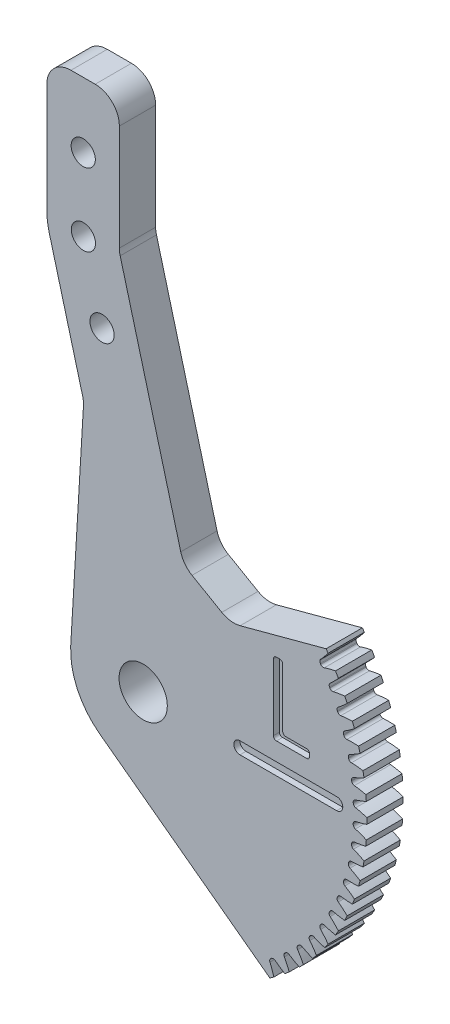
SolidWorks part; units mm, degrees
material "Delrin 2700 NC010, Low Viscosity Acetal Copolymer (SS)"
ref_plane "Front Plane" through (0, 0, 0) normal (0, 0, 1) x (1, 0, 0)
ref_plane "Top Plane" through (0, 0, 0) normal (0, 1, 0) x (1, 0, 0)
ref_plane "Right Plane" through (0, 0, 0) normal (1, 0, 0) x (0, 0, -1)
sketch "Sketch2" plane through (0, 0, 0) normal (0, 0, 1) x (1, 0, 0)
  circle A0 centre (0, 0) radius 60.325
  dimension "D1" = 120.65
extrude "Boss-Extrude2" add sketch "Sketch2" along normal mid plane 9.525
sketch "Sketch3" plane through (0, 0, 4.7625) normal (0, 0, 1) x (1, 0, 0)
  line L0 (0, 0) -> (-57.8242, 215.8028) construction
  line L1 (0, 0) -> (60.325, 0) construction
  line L2 (-15.6133, 58.2695) -> (-24.6525, 92.0044)
  line L3 (-24.6525, 92.0044) -> (-6.2516, 96.9349)
  line L4 (-6.2516, 96.9349) -> (3.5866, 60.2183)
  circle A0 centre (0, 0) radius 60.325 construction
  arc A1 (3.5866, 60.2183) -> (-15.6133, 58.2695) centre (0, 0) ccw
  point P9 (0, 0)
  point P11 (0, 0)
  dimension "D1" = 105
  dimension "D2" = 19.05
  dimension "D3" = 95.25
extrude "Boss-Extrude3" add sketch "Sketch3" against normal up to surface (9.525 mm away) up to face at (60.325, 0, -4.7625)
sketch "Sketch4" plane through (0, 0, 4.7625) normal (0, 0, 1) x (1, 0, 0)
  line L0 (-6.2516, 96.9349) -> (-25.3016, 96.9349)
  line L1 (-25.3016, 96.9349) -> (-25.3016, 131.8599)
  line L2 (-25.3016, 131.8599) -> (-6.2516, 131.8599)
  line L3 (-6.2516, 131.8599) -> (-6.2516, 96.9349)
  line L4 (3.5866, 60.2183) -> (-6.2516, 96.9349) construction
  dimension "D3" = 34.925
  dimension "D1" = 19.05
  dimension "D2" = 165
extrude "Boss-Extrude4" add sketch "Sketch4" against normal up to surface (9.525 mm away) separate body
sketch "Sketch5" plane through (0, 0, 4.7625) normal (0, 0, 1) x (1, 0, 0)
  line L0 (-25.3016, 96.9349) -> (-6.2516, 96.9349) construction
  line L1 (-6.2516, 96.9349) -> (-24.6525, 92.0044) construction
  line L2 (-25.3016, 96.9349) -> (-6.2516, 96.9349)
  line L3 (-6.2516, 96.9349) -> (-24.6525, 92.0044)
  arc A0 (-25.3016, 96.9349) -> (-24.6525, 92.0044) centre (-6.2516, 96.9349) ccw
extrude "Boss-Extrude5" add sketch "Sketch5" against normal up to surface (9.525 mm away)
hole_wizard "1/2 (0.5) Diameter Hole1" positions "Sketch6" profile "Sketch7" hole size "1/2" standard "ANSI Inch" end condition through all
sketch "Sketch6" plane through (0, 0, 4.7625) normal (0, 0, 1) x (1, 0, 0)
  point P0 (0, 0)
sketch "Sketch7" plane through (0, 0, 4.7625) normal (1, 0, 0) x (0, -1, 0)
  line L0 (0, 0) -> (0, 9.525)
  line L1 (0, 9.525) -> (6.3373, 9.525)
  line L2 (6.3373, 9.525) -> (6.3373, 0)
  line L5 (6.3373, 0) -> (0, 0)
  line L11 (0, -6.35) -> (0, 107.95) construction
  dimension "Thru Hole Dia." = 12.6746
  dimension "Thru Hole Depth" = 9.525
sketch "Sketch8" plane through (0, 0, 4.7625) normal (0, 0, 1) x (1, 0, 0)
  line L0 (0, 0) -> (58.2695, 15.6133) construction
  line L1 (-24.6525, 92.0044) -> (-15.6133, 58.2695) construction
  line L2 (22.9188, 27.0957) -> (49.653, 34.2591)
  line L3 (22.9188, 27.0957) -> (10.548, 34.2381)
  line L4 (3.5866, 60.2183) -> (10.548, 34.2381)
  line L5 (3.5866, 60.2183) -> (-6.2516, 96.9349) construction
  line L7 (-5.2387, 19.5509) -> (53.0308, 35.1642) construction
  arc A0 (-15.6133, 58.2695) -> (3.5866, 60.2183) centre (0, 0) ccw construction
  arc A1 (49.653, 34.2591) -> (3.5866, 60.2183) centre (0, 0) ccw
  dimension "D2" = 45
  dimension "D3" = 34.925
  dimension "D1" = 20.2406
extrude "Cut-Extrude1" cut sketch "Sketch8" against normal through all
sketch "Sketch9" plane through (0, 0, 4.7625) normal (0, 0, 1) x (1, 0, 0)
  line L0 (-15.6133, 58.2695) -> (-19.0163, 1.1326)
  line L1 (0, 0) -> (58.2695, 15.6133) construction
  line L2 (-24.6525, 92.0044) -> (-15.6133, 58.2695) construction
  line L3 (0, 0) -> (34.601, -49.4153) construction
  line L4 (34.601, -49.4153) -> (-11.3558, -15.2954)
  arc A0 (-19.0163, 1.1326) -> (-11.3558, -15.2954) centre (0, 0) ccw
  arc A1 (-15.6133, 58.2695) -> (49.653, 34.2591) centre (0, 0) ccw construction
  arc A2 (-15.6133, 58.2695) -> (34.601, -49.4153) centre (0, 0) ccw
  dimension "D1" = 38.1
  dimension "D2" = 70
extrude "Cut-Extrude2" cut sketch "Sketch9" against normal through all
sketch "Sketch10" plane through (0, 0, 4.7625) normal (0, 0, 1) x (1, 0, 0)
  line L0 (0, 0) -> (60.325, 0) construction
  circle A0 centre (0, 0) radius 6.3373 construction
  arc A1 (34.601, -49.4153) -> (49.653, 34.2591) centre (0, 0) ccw construction
  point P7 (58.7375, 0)
  line B0 (25.5768, -48.9104) -> (25.3948, -49.0051)
  line B1 (21.2167, -50.9534) -> (21.0271, -51.032)
  line B2 (16.695, -52.6087) -> (16.4993, -52.6704)
  line B3 (15.9333, -56.5352) -> (15.2024, -56.7361)
  line B4 (15.2024, -56.7361) -> (16.435, -61.3363)
  line B5 (44.9013, 44.9013) -> (41.5337, 41.5337)
  line B6 (41.5337, 41.5337) -> (42.0662, 40.9942)
  line B7 (40.624, 37.3642) -> (40.7627, 37.2129)
  line B8 (43.726, 33.6814) -> (43.8509, 33.5186)
  line B9 (46.4951, 29.7423) -> (46.6054, 29.5692)
  line B10 (48.9104, 25.5768) -> (49.0051, 25.3948)
  line B11 (50.9534, 21.2167) -> (51.032, 21.0271)
  line B12 (52.6087, 16.695) -> (52.6704, 16.4993)
  line B13 (53.8636, 12.0464) -> (53.908, 11.846)
  line B14 (54.7085, 7.306) -> (54.7353, 7.1025)
  line B15 (55.1371, 2.51) -> (55.146, 2.305)
  line B16 (55.146, -2.305) -> (55.1371, -2.51)
  line B17 (54.7353, -7.1025) -> (54.7085, -7.306)
  line B18 (53.908, -11.846) -> (53.8636, -12.0464)
  line B19 (52.6704, -16.4993) -> (52.6087, -16.695)
  line B20 (51.032, -21.0271) -> (50.9534, -21.2167)
  line B21 (49.0051, -25.3948) -> (48.9104, -25.5768)
  line B22 (46.6054, -29.5692) -> (46.4951, -29.7423)
  line B23 (43.8509, -33.5186) -> (43.726, -33.6814)
  line B24 (40.7627, -37.2129) -> (40.624, -37.3642)
  line B25 (37.3642, -40.624) -> (37.2129, -40.7627)
  line B26 (33.6814, -43.726) -> (33.5186, -43.8509)
  line B27 (29.7423, -46.4951) -> (29.5692, -46.6054)
  circle B28 centre (0, 0) radius 7.9375 construction
  arc B29 (28.7098, -51.2429) -> (30.0228, -50.4849) centre (0, 0) ccw
  arc B30 (26.5405, -49.0894) -> (28.7098, -51.2429) centre (43.565, -34.1095) ccw
  arc B31 (26.5405, -49.0894) -> (25.5768, -48.9104) centre (25.9446, -49.6138) ccw
  arc B32 (25.3948, -49.0051) -> (24.9887, -49.8973) centre (25.76, -49.7099) ccw
  arc B33 (25.5085, -52.9095) -> (24.9887, -49.8973) centre (2.953, -55.2508) ccw
  arc B34 (24.1345, -53.5502) -> (25.5085, -52.9095) centre (0, 0) ccw
  arc B35 (22.1611, -51.2158) -> (24.1345, -53.5502) centre (40.4264, -37.7767) ccw
  arc B36 (22.1611, -51.2158) -> (21.2167, -50.9534) centre (21.5218, -51.6862) ccw
  arc B37 (21.0271, -51.032) -> (20.5447, -51.8853) centre (21.3295, -51.7659) ccw
  arc B38 (20.8, -54.9313) -> (20.5447, -51.8853) centre (-1.8736, -55.2979) ccw
  arc B39 (19.3754, -55.4499) -> (20.8, -54.9313) centre (0, 0) ccw
  arc B40 (17.613, -52.9524) -> (19.3754, -55.4499) centre (36.9801, -41.1563) ccw
  arc B41 (17.613, -52.9524) -> (16.695, -52.6087) centre (16.9351, -53.3653) ccw
  arc B42 (16.4993, -52.6704) -> (15.9445, -53.4785) centre (16.7366, -53.4279) ccw
  arc B43 (15.9333, -56.5352) -> (15.9445, -53.4785) centre (-6.686, -54.9242) ccw
  arc B44 (16.435, -61.3363) -> (44.9013, 44.9013) centre (0, 0) ccw
  arc B45 (40.5475, 38.3415) -> (42.0662, 40.9942) centre (21.6718, 50.9087) ccw
  arc B46 (40.5475, 38.3415) -> (40.624, 37.3642) centre (41.2083, 37.9016) ccw
  arc B47 (40.7627, 37.2129) -> (41.7295, 37.0516) centre (41.3489, 37.7481) ccw
  arc B48 (44.5045, 38.3333) -> (41.7295, 37.0516) centre (52.6038, 17.1524) ccw
  arc B49 (45.479, 37.1719) -> (44.5045, 38.3333) centre (0, 0) ccw
  arc B50 (43.7349, 34.6616) -> (45.479, 37.1719) centre (26.0264, 48.8262) ccw
  arc B51 (43.7349, 34.6616) -> (43.726, 33.6814) centre (44.3548, 34.1658) ccw
  arc B52 (43.8509, 33.5186) -> (44.8, 33.2736) centre (44.4815, 34.0007) ccw
  arc B53 (47.6762, 34.3086) -> (44.8, 33.2736) centre (53.8986, 12.5024) ccw
  arc B54 (48.5457, 33.0667) -> (47.6762, 34.3086) centre (0, 0) ccw
  arc B55 (46.5895, 30.718) -> (48.5457, 33.0667) centre (30.1828, 46.3721) ccw
  arc B56 (46.5895, 30.718) -> (46.4951, 29.7423) centre (47.1638, 30.17) ccw
  arc B57 (46.6054, 29.5692) -> (47.5295, 29.2424) centre (47.2756, 29.9945) ccw
  arc B58 (50.4849, 30.0228) -> (47.5295, 29.2424) centre (54.7832, 7.7572) ccw
  arc B59 (51.2429, 28.7098) -> (50.4849, 30.0228) centre (0, 0) ccw
  arc B60 (49.0894, 26.5405) -> (51.2429, 28.7098) centre (34.1095, 43.565) ccw
  arc B61 (49.0894, 26.5405) -> (48.9104, 25.5768) centre (49.6138, 25.9446) ccw
  arc B62 (49.0051, 25.3948) -> (49.8973, 24.9887) centre (49.7099, 25.76) ccw
  arc B63 (52.9095, 25.5085) -> (49.8973, 24.9887) centre (55.2508, 2.953) ccw
  arc B64 (53.5502, 24.1345) -> (52.9095, 25.5085) centre (0, 0) ccw
  arc B65 (51.2158, 22.1611) -> (53.5502, 24.1345) centre (37.7767, 40.4264) ccw
  arc B66 (51.2158, 22.1611) -> (50.9534, 21.2167) centre (51.6862, 21.5218) ccw
  arc B67 (51.032, 21.0271) -> (51.8853, 20.5447) centre (51.7659, 21.3295) ccw
  arc B68 (54.9313, 20.8) -> (51.8853, 20.5447) centre (55.2979, -1.8736) ccw
  arc B69 (55.4499, 19.3754) -> (54.9313, 20.8) centre (0, 0) ccw
  arc B70 (52.9524, 17.613) -> (55.4499, 19.3754) centre (41.1563, 36.9801) ccw
  arc B71 (52.9524, 17.613) -> (52.6087, 16.695) centre (53.3653, 16.9351) ccw
  arc B72 (52.6704, 16.4993) -> (53.4785, 15.9445) centre (53.4279, 16.7366) ccw
  arc B73 (56.5352, 15.9333) -> (53.4785, 15.9445) centre (54.9242, -6.686) ccw
  arc B74 (56.9275, 14.4689) -> (56.5352, 15.9333) centre (0, 0) ccw
  arc B75 (54.2859, 12.9309) -> (56.9275, 14.4689) centre (44.2227, 33.2523) ccw
  arc B76 (54.2859, 12.9309) -> (53.8636, 12.0464) centre (54.6382, 12.2196) ccw
  arc B77 (53.908, 11.846) -> (54.6646, 11.2228) centre (54.6832, 12.0164) ccw
  arc B78 (57.7087, 10.9453) -> (54.6646, 11.2228) centre (54.1325, -11.4475) ccw
  arc B79 (57.972, 9.4523) -> (57.7087, 10.9453) centre (0, 0) ccw
  arc B80 (55.2064, 8.1504) -> (57.972, 9.4523) centre (46.9526, 29.2715) ccw
  arc B81 (55.2064, 8.1504) -> (54.7085, 7.306) centre (55.4953, 7.4111) ccw
  arc B82 (54.7353, 7.1025) -> (55.4347, 6.4158) centre (55.5225, 7.2047) ccw
  arc B83 (58.443, 5.874) -> (55.4347, 6.4158) centre (52.9287, -16.1219) ccw
  arc B84 (58.5752, 4.3638) -> (58.443, 5.874) centre (0, 0) ccw
  arc B85 (55.7067, 3.3078) -> (58.5752, 4.3638) centre (49.3251, 25.068) ccw
  arc B86 (55.7067, 3.3078) -> (55.1371, 2.51) centre (55.93, 2.5461) ccw
  arc B87 (55.146, 2.305) -> (55.783, 1.5599) centre (55.9391, 2.3382) ccw
  arc B88 (58.7326, 0.758) -> (55.783, 1.5599) centre (51.3222, -20.6736) ccw
  arc B89 (58.7326, -0.758) -> (58.7326, 0.758) centre (0, 0) ccw
  arc B90 (55.783, -1.5599) -> (58.7326, -0.758) centre (51.3222, 20.6736) ccw
  arc B91 (55.783, -1.5599) -> (55.146, -2.305) centre (55.9391, -2.3382) ccw
  arc B92 (55.1371, -2.51) -> (55.7067, -3.3078) centre (55.93, -2.5461) ccw
  arc B93 (58.5752, -4.3638) -> (55.7067, -3.3078) centre (49.3251, -25.068) ccw
  arc B94 (58.443, -5.874) -> (58.5752, -4.3638) centre (0, 0) ccw
  arc B95 (55.4347, -6.4158) -> (58.443, -5.874) centre (52.9287, 16.1219) ccw
  arc B96 (55.4347, -6.4158) -> (54.7353, -7.1025) centre (55.5225, -7.2047) ccw
  arc B97 (54.7085, -7.306) -> (55.2064, -8.1504) centre (55.4953, -7.4111) ccw
  arc B98 (57.972, -9.4523) -> (55.2064, -8.1504) centre (46.9526, -29.2715) ccw
  arc B99 (57.7087, -10.9453) -> (57.972, -9.4523) centre (0, 0) ccw
  arc B100 (54.6646, -11.2228) -> (57.7087, -10.9453) centre (54.1325, 11.4475) ccw
  arc B101 (54.6646, -11.2228) -> (53.908, -11.846) centre (54.6832, -12.0164) ccw
  arc B102 (53.8636, -12.0464) -> (54.2859, -12.9309) centre (54.6382, -12.2196) ccw
  arc B103 (56.9275, -14.4689) -> (54.2859, -12.9309) centre (44.2227, -33.2523) ccw
  arc B104 (56.5352, -15.9333) -> (56.9275, -14.4689) centre (0, 0) ccw
  arc B105 (53.4785, -15.9445) -> (56.5352, -15.9333) centre (54.9242, 6.686) ccw
  arc B106 (53.4785, -15.9445) -> (52.6704, -16.4993) centre (53.4279, -16.7366) ccw
  arc B107 (52.6087, -16.695) -> (52.9524, -17.613) centre (53.3653, -16.9351) ccw
  arc B108 (55.4499, -19.3754) -> (52.9524, -17.613) centre (41.1563, -36.9801) ccw
  arc B109 (54.9313, -20.8) -> (55.4499, -19.3754) centre (0, 0) ccw
  arc B110 (51.8853, -20.5447) -> (54.9313, -20.8) centre (55.2979, 1.8736) ccw
  arc B111 (51.8853, -20.5447) -> (51.032, -21.0271) centre (51.7659, -21.3295) ccw
  arc B112 (50.9534, -21.2167) -> (51.2158, -22.1611) centre (51.6862, -21.5218) ccw
  arc B113 (53.5502, -24.1345) -> (51.2158, -22.1611) centre (37.7767, -40.4264) ccw
  arc B114 (52.9095, -25.5085) -> (53.5502, -24.1345) centre (0, 0) ccw
  arc B115 (49.8973, -24.9887) -> (52.9095, -25.5085) centre (55.2508, -2.953) ccw
  arc B116 (49.8973, -24.9887) -> (49.0051, -25.3948) centre (49.7099, -25.76) ccw
  arc B117 (48.9104, -25.5768) -> (49.0894, -26.5405) centre (49.6138, -25.9446) ccw
  arc B118 (51.2429, -28.7098) -> (49.0894, -26.5405) centre (34.1095, -43.565) ccw
  arc B119 (50.4849, -30.0228) -> (51.2429, -28.7098) centre (0, 0) ccw
  arc B120 (47.5295, -29.2424) -> (50.4849, -30.0228) centre (54.7832, -7.7572) ccw
  arc B121 (47.5295, -29.2424) -> (46.6054, -29.5692) centre (47.2756, -29.9945) ccw
  arc B122 (46.4951, -29.7423) -> (46.5895, -30.718) centre (47.1638, -30.17) ccw
  arc B123 (48.5457, -33.0667) -> (46.5895, -30.718) centre (30.1828, -46.3721) ccw
  arc B124 (47.6762, -34.3086) -> (48.5457, -33.0667) centre (0, 0) ccw
  arc B125 (44.8, -33.2736) -> (47.6762, -34.3086) centre (53.8986, -12.5024) ccw
  arc B126 (44.8, -33.2736) -> (43.8509, -33.5186) centre (44.4815, -34.0007) ccw
  arc B127 (43.726, -33.6814) -> (43.7349, -34.6616) centre (44.3548, -34.1658) ccw
  arc B128 (45.479, -37.1719) -> (43.7349, -34.6616) centre (26.0264, -48.8262) ccw
  arc B129 (44.5045, -38.3333) -> (45.479, -37.1719) centre (0, 0) ccw
  arc B130 (41.7295, -37.0516) -> (44.5045, -38.3333) centre (52.6038, -17.1524) ccw
  arc B131 (41.7295, -37.0516) -> (40.7627, -37.2129) centre (41.3489, -37.7481) ccw
  arc B132 (40.624, -37.3642) -> (40.5475, -38.3415) centre (41.2083, -37.9016) ccw
  arc B133 (42.0662, -40.9942) -> (40.5475, -38.3415) centre (21.6718, -50.9087) ccw
  arc B134 (40.9942, -42.0662) -> (42.0662, -40.9942) centre (0, 0) ccw
  arc B135 (38.3415, -40.5475) -> (40.9942, -42.0662) centre (50.9087, -21.6718) ccw
  arc B136 (38.3415, -40.5475) -> (37.3642, -40.624) centre (37.9016, -41.2083) ccw
  arc B137 (37.2129, -40.7627) -> (37.0516, -41.7295) centre (37.7481, -41.3489) ccw
  arc B138 (38.3333, -44.5045) -> (37.0516, -41.7295) centre (17.1524, -52.6038) ccw
  arc B139 (37.1719, -45.479) -> (38.3333, -44.5045) centre (0, 0) ccw
  arc B140 (34.6616, -43.7349) -> (37.1719, -45.479) centre (48.8262, -26.0264) ccw
  arc B141 (34.6616, -43.7349) -> (33.6814, -43.726) centre (34.1658, -44.3548) ccw
  arc B142 (33.5186, -43.8509) -> (33.2736, -44.8) centre (34.0007, -44.4815) ccw
  arc B143 (34.3086, -47.6762) -> (33.2736, -44.8) centre (12.5024, -53.8986) ccw
  arc B144 (33.0667, -48.5457) -> (34.3086, -47.6762) centre (0, 0) ccw
  arc B145 (30.718, -46.5895) -> (33.0667, -48.5457) centre (46.3721, -30.1828) ccw
  arc B146 (30.718, -46.5895) -> (29.7423, -46.4951) centre (30.17, -47.1638) ccw
  arc B147 (29.5692, -46.6054) -> (29.2424, -47.5295) centre (29.9945, -47.2756) ccw
  arc B148 (30.0228, -50.4849) -> (29.2424, -47.5295) centre (7.7572, -54.7832) ccw
sketch_block_instance "Block1-1"
sketch_block "Block1"
extrude "Cut-Extrude3" cut sketch "Sketch10" against normal blind 12.7
hole_wizard "1/4 (0.25) Diameter Hole1" positions "Sketch11" profile "Sketch12" hole size "1/4" standard "ANSI Inch" end condition through all
sketch "Sketch11" plane through (0, 0, 4.7625) normal (0, 0, 1) x (1, 0, 0)
  line L0 (-15.7766, 131.8599) -> (-15.6951, 95.6917) construction
  line L1 (-6.2516, 131.8599) -> (-25.3016, 131.8599) construction
  line L2 (-15.6951, 95.6917) -> (-6.4128, 60.7347) construction
  line L4 (-25.1387, 94.4484) -> (-6.2516, 96.9349) construction
  line L6 (-15.6133, 58.2695) -> (2.7876, 63.2) construction
  line L7 (10.548, 34.2381) -> (-6.2516, 96.9349) construction
  arc A0 (-25.3016, 96.9349) -> (-24.6525, 92.0044) centre (-6.2516, 96.9349) ccw construction
  point P0 (-15.7381, 114.7417)
  point P2 (-15.6951, 95.6917)
  point P4 (-10.8061, 77.2797)
  point P29 (0, 0)
  dimension "D1" = 19.05
  dimension "D2" = 19.05
sketch "Sketch12" plane through (-15.7381, 114.7417, 4.7625) normal (1, 0, 0) x (0, -1, 0)
  line L0 (0, 0) -> (0, 9.525)
  line L1 (0, 9.525) -> (3.175, 9.525)
  line L2 (3.175, 9.525) -> (3.175, 0)
  line L5 (3.175, 0) -> (0, 0)
  line L11 (0, -6.35) -> (0, 107.95) construction
  dimension "Thru Hole Dia." = 6.35
  dimension "Thru Hole Depth" = 9.525
fillet "Fillet1" radius 6.35 6 edges at (22.9188, 27.0957, 0) (10.548, 34.2381, 0) (-6.2516, 96.9349, 0) (-6.2516, 131.8599, 0) (-25.3016, 131.8599, 0) (-15.6133, 58.2695, 0)
sketch "Sketch13" plane through (0, 0, 4.7625) normal (0, 0, 1) x (1, 0, 0)
  line L0 (0, 0) -> (82.2868, 0) construction
  line L1 (25.4, 0) -> (50.8, 0) construction
  line L2 (25.4, 1.6002) -> (50.8, 1.6002)
  line L3 (25.4, -1.6002) -> (50.8, -1.6002)
  arc A0 (25.4, 1.6002) -> (25.4, -1.6002) centre (25.4, 0) ccw
  arc A1 (50.8, -1.6002) -> (50.8, 1.6002) centre (50.8, 0) ccw
  circle A2 centre (0, 0) radius 6.3373 construction
  point P5 (38.1, 0)
  dimension "D1" = 1.6002
  dimension "D3" = 25.4
  dimension "D2" = 25.4
extrude "Cut-Extrude4" cut sketch "Sketch13" against normal blind 1.5875
sketch "Sketch14" plane through (0, 0, 4.7625) normal (0, 0, 1) x (1, 0, 0)
  text T0 "<b>L</b>" font "Century Gothic" height 19.05
  dimension "D1" = 31.75
  dimension "D2" = 6.35
extrude "Cut-Extrude5" cut sketch "Sketch14" against normal blind 1.5875
fillet "Fillet2" radius 0.7937 6 edges at (43.7173, 6.35, 3.9688) (43.7173, 8.5481, 3.9688) (36.6346, 8.5481, 3.9688) (36.6346, 25.4, 3.9688) (34.1923, 6.35, 3.9688) (34.1923, 25.4, 3.9688)
equation "\"D1@Sketch2\"=2.375*2"
equation "\"D1@Sketch8\"=0.8125in-.015625"
equation "\"D2@Sketch11\"=\"D1@Sketch11\""
equation "\"D3@Sketch4\"=1.250in+.125"
